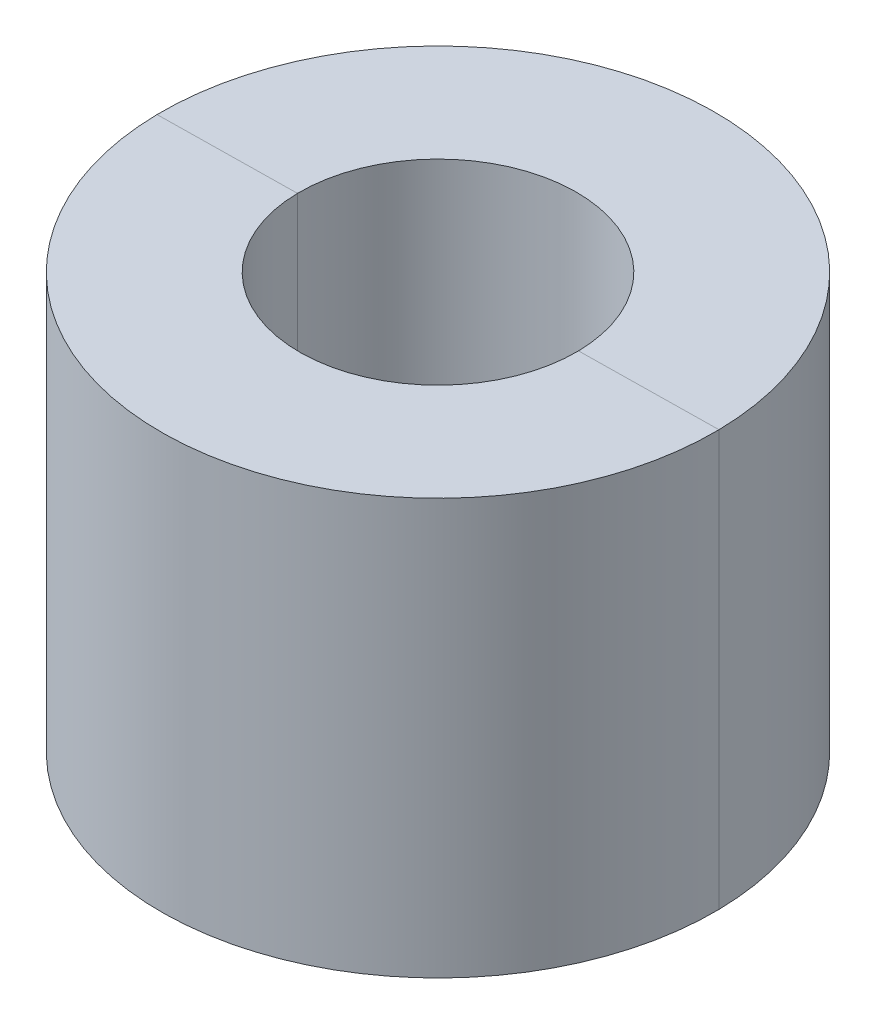
SolidWorks part; units mm, degrees
material "Copper"
ref_plane "Front Plane" through (0, 0, 0) normal (0, 0, 1) x (1, 0, 0)
ref_plane "Top Plane" through (0, 0, 0) normal (0, 1, 0) x (1, 0, 0)
ref_plane "Right Plane" through (0, 0, 0) normal (1, 0, 0) x (0, 0, -1)
sketch "Sketch1" plane through (0, 0, 0) normal (0, 1, 0) x (1, 0, 0)
  circle A0 centre (0, 0) radius 20
  dimension "D1" = 40
extrude "Extrude-Thin1" add sketch "Sketch1" along normal blind 30 thin thin type one direction reverse wall 10
sketch "Sketch2" plane through (0, 30, 0) normal (0, 1, 0) x (1, 0, 0)
  line L0 (-26.5126, -0.3864) -> (28.8296, 0.4202)
split "Split1" trim tools "Sketch2" bodies to split 101 resulting bodies 103 104
